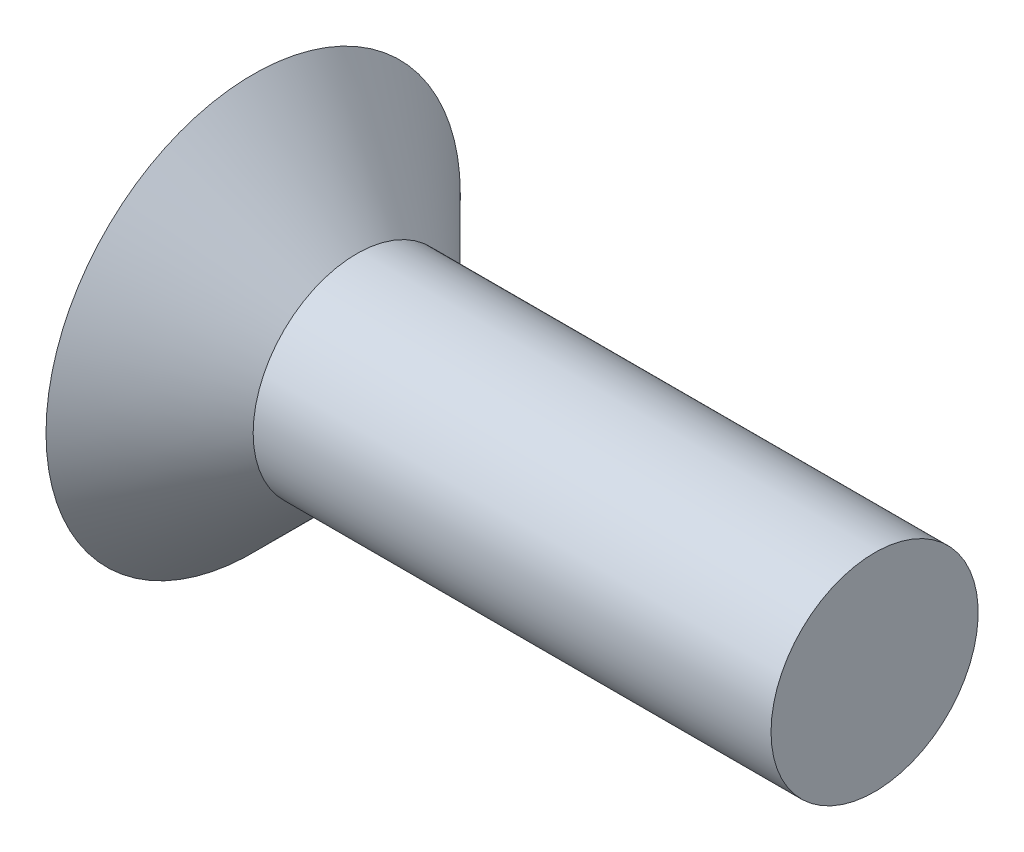
SolidWorks part; units mm, degrees
ref_plane "前视基准面" through (0, 0, 0) normal (0, 0, 1) x (1, 0, 0)
ref_plane "上视基准面" through (0, 0, 0) normal (0, 1, 0) x (1, 0, 0)
ref_plane "右视基准面" through (0, 0, 0) normal (1, 0, 0) x (0, 0, -1)
sketch "草图1" plane through (0, 0, 0) normal (0, 1, 0) x (1, 0, 0)
  line L0 (-15.3051, 0) -> (-6.3051, 0)
  line L1 (-13.8051, -1.5) -> (-6.3051, -1.5) construction
  line L2 (-13.8051, 1.5) -> (-6.3051, 1.5)
  line L3 (-13.8051, 1.5) -> (-15.3051, 3)
  line L4 (-13.8051, -1.5) -> (-15.3051, -3) construction
  line L5 (-15.3051, 3) -> (-15.3051, 0)
  line L6 (-15.3051, 0) -> (-15.3051, -3) construction
  line L7 (-6.3051, 0) -> (-6.3051, -1.5) construction
  line L8 (-6.3051, 0) -> (-6.3051, 1.5)
  dimension "D4" = 6
  dimension "D5" = 9
  dimension "D1" = 90
  dimension "D2" = 3
revolve "旋转3" add sketch "草图1" angle 360 about L0
